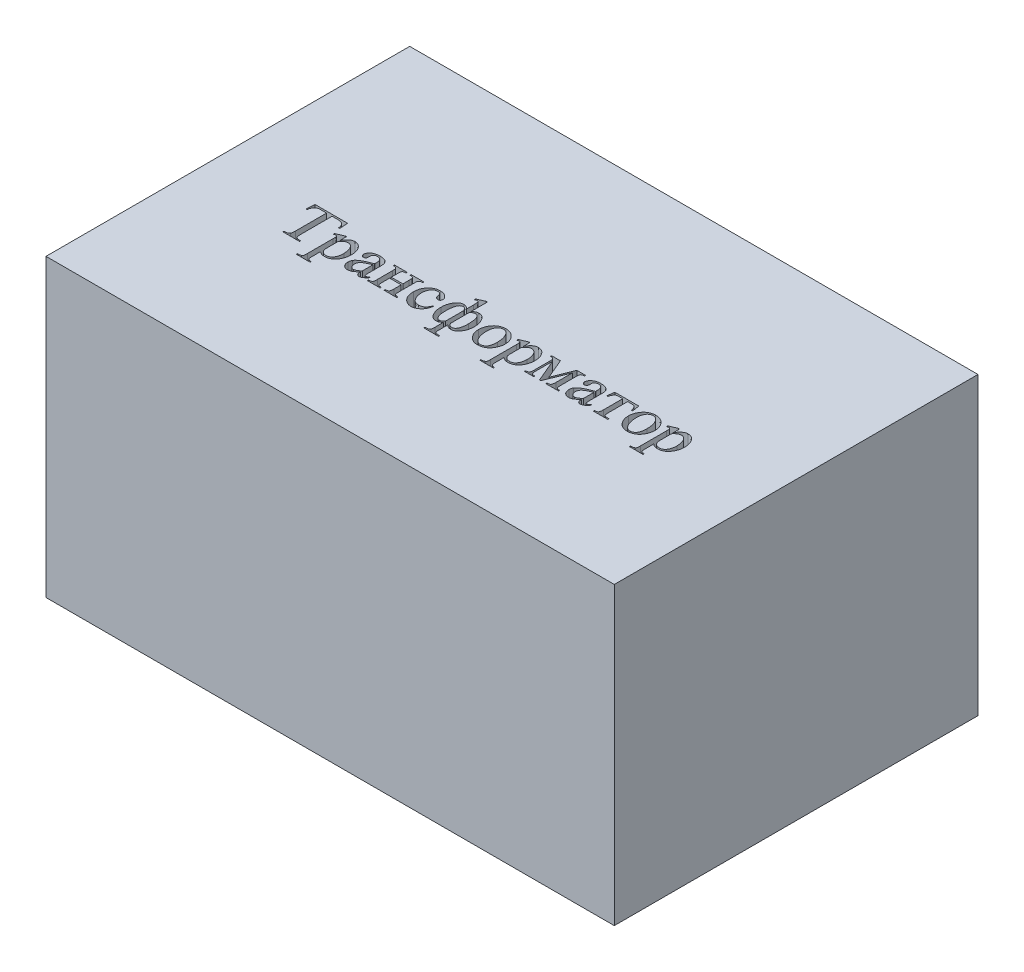
SolidWorks part; units mm, degrees
material "1023 Листовая углеродистая сталь (SS)"
ref_plane "Спереди" through (0, 0, 0) normal (0, 0, 1) x (1, 0, 0)
ref_plane "Сверху" through (0, 0, 0) normal (0, 1, 0) x (1, 0, 0)
ref_plane "Справа" through (0, 0, 0) normal (1, 0, 0) x (0, 0, -1)
sketch "Эскиз1" plane through (0, 0, 0) normal (0, 1, 0) x (1, 0, 0)
  line L1 (-25, -16) -> (25, -16)
  line L2 (-25, -16) -> (-25, 16)
  line L3 (-25, 16) -> (25, 16)
  line L4 (25, -16) -> (25, 16)
  line L5 (-25, -16) -> (25, 16) construction
  line L6 (-25, 16) -> (25, -16) construction
  point P0 (0, 0)
  dimension "D1" = 50
  dimension "D2" = 32
extrude "Бобышка-Вытянуть1" add sketch "Эскиз1" along normal blind 26
sketch "Эскиз2" plane through (0, 26, 0) normal (0, 1, 0) x (1, 0, 0)
  text T0 "Трансформатор" font "Times New Roman" height 3.5
extrude "Вырез-Вытянуть1" cut sketch "Эскиз2" against normal blind 2
